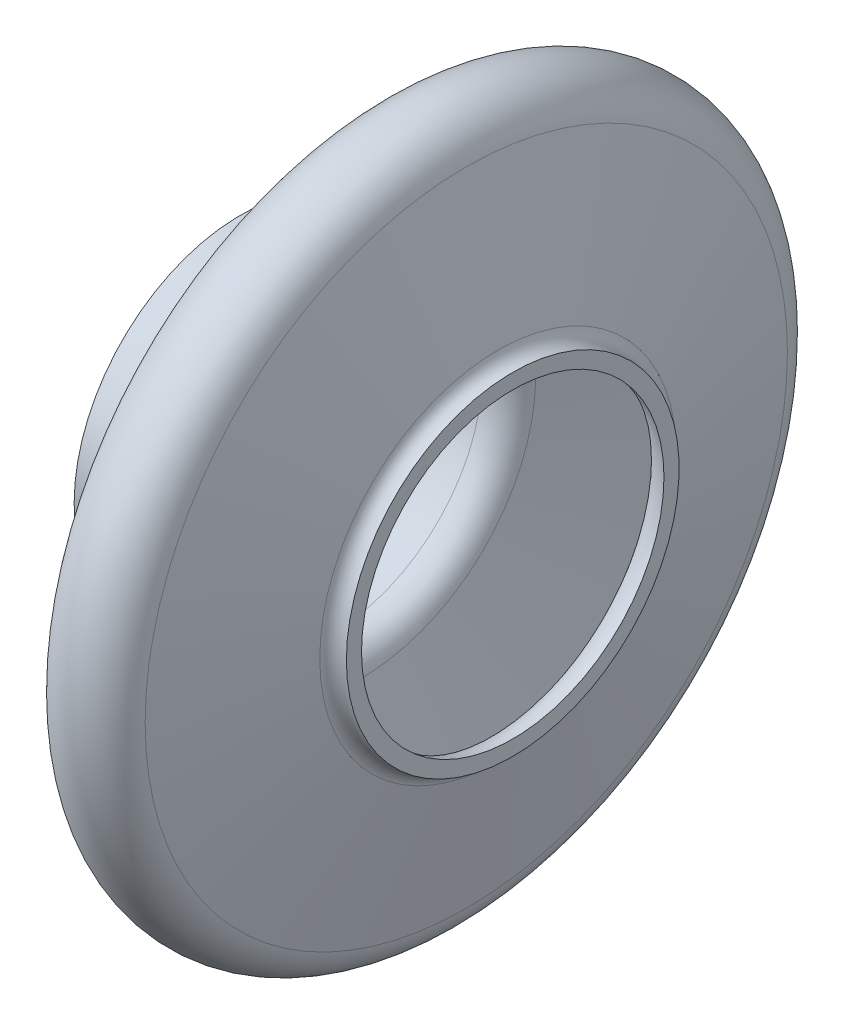
SolidWorks part; units mm, degrees
ref_plane "Front Plane" through (0, 0, 0) normal (0, 0, 1) x (1, 0, 0)
ref_plane "Top Plane" through (0, 0, 0) normal (0, 1, 0) x (1, 0, 0)
ref_plane "Right Plane" through (0, 0, 0) normal (1, 0, 0) x (0, 0, -1)
sketch "Sketch2" plane through (0, 0, 0) normal (0, 1, 0) x (1, 0, 0)
  line L0 (0, 0) -> (35.1605, 0) construction
  line L1 (0, 0) -> (0, 10) construction
  line L2 (0, 10) -> (-6, 10)
  line L3 (-12, 0) -> (-12, 10) construction
  line L4 (-7.9526, 11.5671) -> (-10.0474, 21.0162)
  line L5 (-16.0474, 11.5671) -> (-13.9526, 21.0162)
  line L6 (-19.9526, 11.5671) -> (-22.0474, 21.0162)
  line L7 (-28.0474, 11.5671) -> (-25.9526, 21.0162)
  line L8 (-31.9526, 11.5671) -> (-34.0474, 21.0162)
  line L9 (-40.0474, 11.5671) -> (-37.9526, 21.0162)
  line L10 (-43.9526, 11.5671) -> (-46.0474, 21.0162)
  line L11 (-52.0474, 11.5671) -> (-49.9526, 21.0162)
  line L12 (-55.9526, 11.5671) -> (-58.0474, 21.0162)
  line L13 (-64.0474, 11.5671) -> (-61.9526, 21.0162)
  line L14 (-6, 10) -> (-18, 10) construction
  line L15 (-66, 10) -> (-72, 10)
  arc A0 (-6, 10) -> (-7.9526, 11.5671) centre (-6, 12) cw
  arc A1 (-10.0474, 21.0162) -> (-13.9526, 21.0162) centre (-12, 20.5833) ccw
  arc A2 (-18, 10) -> (-16.0474, 11.5671) centre (-18, 12) ccw
  arc A3 (-18, 10) -> (-19.9526, 11.5671) centre (-18, 12) cw
  arc A4 (-22.0474, 21.0162) -> (-25.9526, 21.0162) centre (-24, 20.5833) ccw
  arc A5 (-30, 10) -> (-28.0474, 11.5671) centre (-30, 12) ccw
  arc A6 (-30, 10) -> (-31.9526, 11.5671) centre (-30, 12) cw
  arc A7 (-34.0474, 21.0162) -> (-37.9526, 21.0162) centre (-36, 20.5833) ccw
  arc A8 (-42, 10) -> (-40.0474, 11.5671) centre (-42, 12) ccw
  arc A9 (-42, 10) -> (-43.9526, 11.5671) centre (-42, 12) cw
  arc A10 (-46.0474, 21.0162) -> (-49.9526, 21.0162) centre (-48, 20.5833) ccw
  arc A11 (-54, 10) -> (-52.0474, 11.5671) centre (-54, 12) ccw
  arc A12 (-54, 10) -> (-55.9526, 11.5671) centre (-54, 12) cw
  arc A13 (-58.0474, 21.0162) -> (-61.9526, 21.0162) centre (-60, 20.5833) ccw
  arc A14 (-66, 10) -> (-64.0474, 11.5671) centre (-66, 12) ccw
  dimension "D2" = 2
  dimension "D1" = 10
  dimension "D3" = 6
  dimension "D4" = 12
  dimension "D5" = 12.5
  dimension "D7" = 12
  dimension "D8" = 6
  dimension "D6" = 5
revolve "Revolve-Thin7" add sketch "Sketch2" angle 360 about L0
